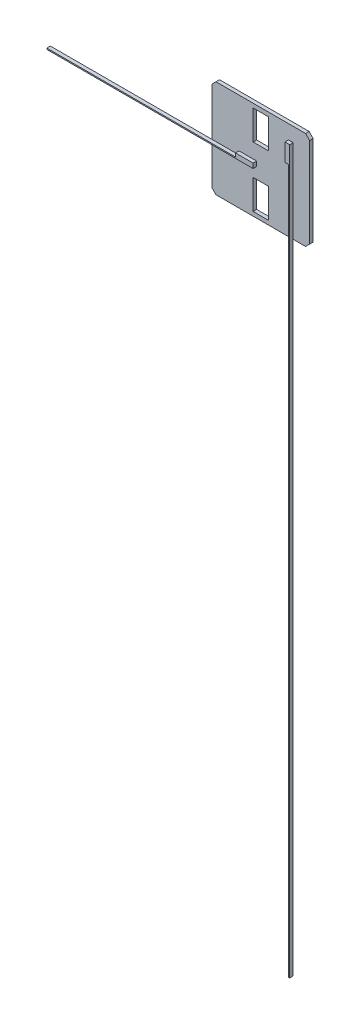
SolidWorks part; units mm, degrees
ref_plane "Front Plane" through (0, 0, 0) normal (0, 0, 1) x (1, 0, 0)
ref_plane "Top Plane" through (0, 0, 0) normal (0, 1, 0) x (1, 0, 0)
ref_plane "Right Plane" through (0, 0, 0) normal (1, 0, 0) x (0, 0, -1)
sketch "Sketch1" plane through (0, 0, 0) normal (0, 0, 1) x (1, 0, 0)
  line L1 (41.5, -41.5) -> (-41.5, -41.5)
  line L2 (41.5, -41.5) -> (41.5, 41.5)
  line L3 (41.5, 41.5) -> (-41.5, 41.5)
  line L4 (-41.5, -41.5) -> (-41.5, 41.5)
  line L5 (41.5, -41.5) -> (-41.5, 41.5) construction
  line L6 (41.5, 41.5) -> (-41.5, -41.5) construction
  point P0 (0, 0)
  dimension "D1" = 83
  dimension "D2" = 83
extrude "Boss-Extrude1" add sketch "Sketch1" along normal blind 3
sketch "Sketch2" plane through (0, 0, 3) normal (0, 0, 1) x (1, 0, 0)
  line L1 (-6.5, 38) -> (6.5, 38)
  line L2 (-6.5, 38) -> (-6.5, 13)
  line L3 (-6.5, 13) -> (6.5, 13)
  line L4 (6.5, 38) -> (6.5, 13)
  line L6 (0, 0) -> (65.5983, 0) construction
  line L7 (6.5, -38) -> (6.5, -13)
  line L8 (-6.5, -13) -> (6.5, -13)
  line L9 (-6.5, -38) -> (-6.5, -13)
  line L10 (-6.5, -38) -> (6.5, -38)
  line L11 (0, 0) -> (0, 70.3331) construction
  dimension "D1" = 13
  dimension "D2" = 6.5
  dimension "D3" = 13
  dimension "D4" = 25
extrude "Cut-Extrude1" cut sketch "Sketch2" against normal blind 3
chamfer "Chamfer1" distance 3.5 angle 45 4 edges at (-41.5, -41.5, 1.5) (41.5, -41.5, 1.5) (41.5, 41.5, 1.5) (-41.5, 41.5, 1.5)
sketch "Sketch3" plane through (0, 0, 3) normal (0, 0, 1) x (1, 0, 0)
  line L0 (41.5, -38) -> (41.5, 38) construction
  line L1 (-18.5, 0.5) -> (-3.5, 0.5)
  line L2 (-18.5, 0.5) -> (-18.5, -2.5)
  line L3 (-18.5, -2.5) -> (-3.5, -2.5)
  line L4 (-3.5, 0.5) -> (-3.5, -2.5)
  line L5 (38, 41.5) -> (-38, 41.5) construction
  line L6 (-41.5, 38) -> (-41.5, -38) construction
  line L7 (23.5, 29.5) -> (26.5, 29.5)
  line L8 (23.5, 29.5) -> (23.5, 14.5)
  line L9 (23.5, 14.5) -> (26.5, 14.5)
  line L10 (26.5, 29.5) -> (26.5, 14.5)
  dimension "D1" = 15
  dimension "D2" = 3
  dimension "D3" = 45
  dimension "D4" = 41
  dimension "D5" = 3
  dimension "D6" = 15
  dimension "D7" = 12
  dimension "D8" = 65
extrude "Boss-Extrude2" add sketch "Sketch3" along normal blind 3
sketch "Sketch5" plane through (0, -2.5, 0) normal (0, -1, 0) x (1, 0, 0)
  line L1 (-178.5, 3) -> (-3.5, 3)
  line L2 (-178.5, 3) -> (-178.5, 6)
  line L3 (-178.5, 6) -> (-3.5, 6)
  line L4 (-3.5, 3) -> (-3.5, 6)
  line L5 (-3.5, 6) -> (-3.5, 3) construction
  dimension "D1" = 3
  dimension "D2" = 175
extrude "Boss-Extrude4" add sketch "Sketch5" along normal blind 1
sketch "Sketch6" plane through (26.5, 0, 0) normal (1, 0, 0) x (0, 0, -1)
  line L1 (-6, 29.5) -> (-3, 29.5)
  line L2 (-6, 29.5) -> (-6, -582.5)
  line L3 (-6, -582.5) -> (-3, -582.5)
  line L4 (-3, 29.5) -> (-3, -582.5)
  dimension "D1" = 612
extrude "Boss-Extrude5" add sketch "Sketch6" along normal blind 1
